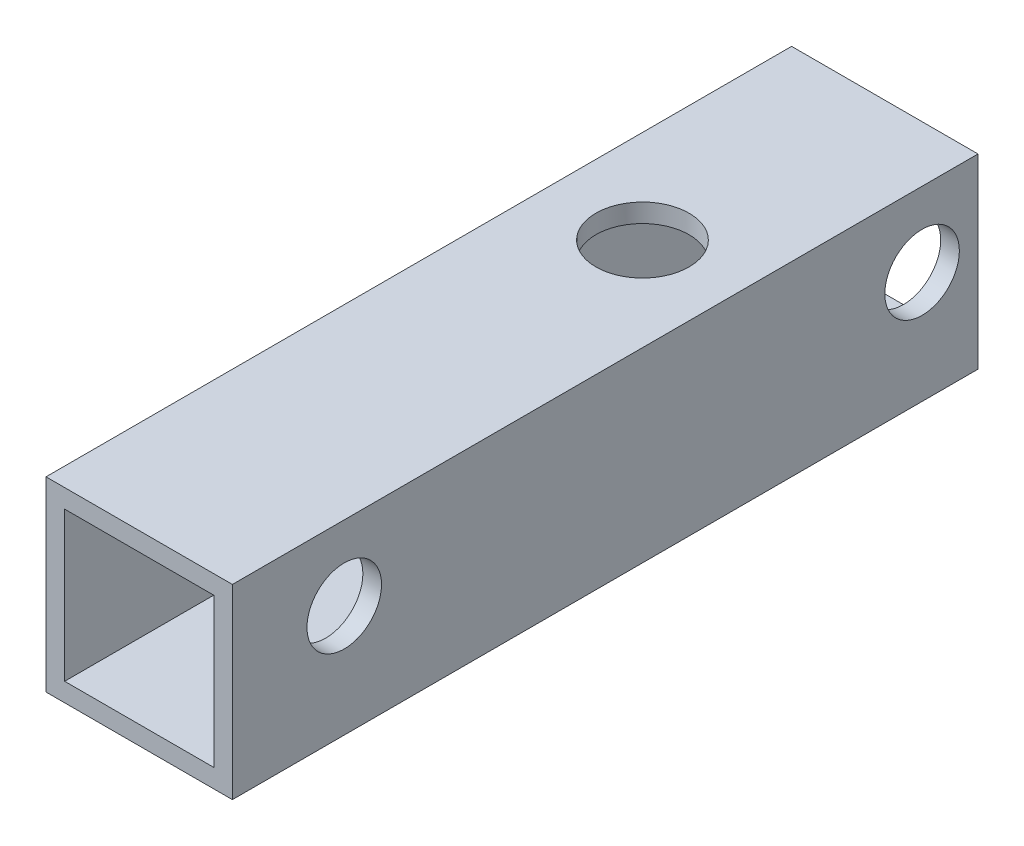
SolidWorks part; units mm, degrees
material "3.0205 (EN AW-1200)"
ref_plane "Ebene vorne" through (0, 0, 0) normal (0, 0, 1) x (1, 0, 0)
ref_plane "Ebene oben" through (0, 0, 0) normal (0, 1, 0) x (1, 0, 0)
ref_plane "Ebene rechts" through (0, 0, 0) normal (1, 0, 0) x (0, 0, -1)
sketch "Skizze1" plane through (0, 0, 0) normal (0, 0, 1) x (1, 0, 0)
  line L1 (5, -5) -> (-5, -5)
  line L2 (5, -5) -> (5, 5)
  line L3 (5, 5) -> (-5, 5)
  line L4 (-5, -5) -> (-5, 5)
  line L5 (5, -5) -> (-5, 5) construction
  line L6 (5, 5) -> (-5, -5) construction
  line L7 (4, -4) -> (-4, -4)
  line L8 (4, -4) -> (4, 4)
  line L9 (4, 4) -> (-4, 4)
  line L10 (-4, -4) -> (-4, 4)
  line L11 (4, -4) -> (-4, 4) construction
  line L12 (4, 4) -> (-4, -4) construction
  point P0 (0, 0)
  point P6 (0, 0)
  dimension "D1" = 10
  dimension "D2" = 1
extrude "Aufsatz-Linear austragen1" add sketch "Skizze1" along normal blind 40
sketch "Skizze2" plane through (5, 0, 0) normal (1, 0, 0) x (0, 0, -1)
  line L0 (-34, 1) -> (-3, 1) construction
  line L1 (-40, -5) -> (0, -5) construction
  line L2 (-40, -5) -> (-40, 5) construction
  circle A0 centre (-34, 1) radius 2
  circle A1 centre (-3, 1) radius 2
  dimension "D4" = 4
  dimension "D1" = 6
  dimension "D2" = 31
  dimension "D3" = 6
extrude "Schnitt-Linear austragen1" cut sketch "Skizze2" against normal through all
sketch "Skizze3" plane through (0, 5, 0) normal (0, 1, 0) x (1, 0, 0)
  line L0 (5, -40) -> (-5, -40) construction
  line L1 (5, -40) -> (5, 0) construction
  circle A0 centre (0, -13) radius 2.5
  dimension "D1" = 5
  dimension "D2" = 27
  dimension "D3" = 5
extrude "Schnitt-Linear austragen2" cut sketch "Skizze3" against normal blind 17
